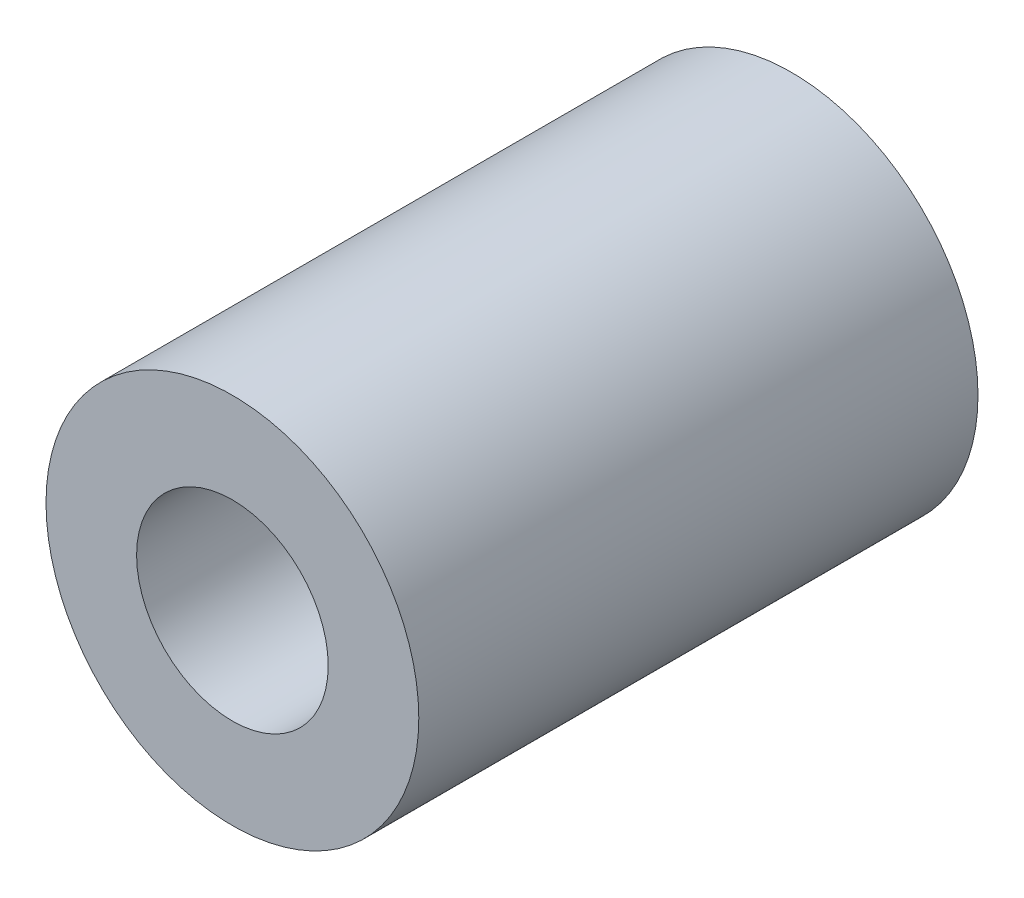
SolidWorks part; units mm, degrees
material "6061-T6 (SS)"
ref_plane "Front Plane" through (0, 0, 0) normal (0, 0, 1) x (1, 0, 0)
ref_plane "Top Plane" through (0, 0, 0) normal (0, 1, 0) x (1, 0, 0)
ref_plane "Right Plane" through (0, 0, 0) normal (1, 0, 0) x (0, 0, -1)
sketch "Sketch1" plane through (0, 0, 0) normal (0, 0, 1) x (1, 0, 0)
  circle A0 centre (0, 0) radius 6.35
  circle A1 centre (0, 0) radius 3.2639
  dimension "D1" = 6.5278
  dimension "D2" = 12.7
extrude "Boss-Extrude1" add sketch "Sketch1" along normal blind 19.05 contours A0 A1
